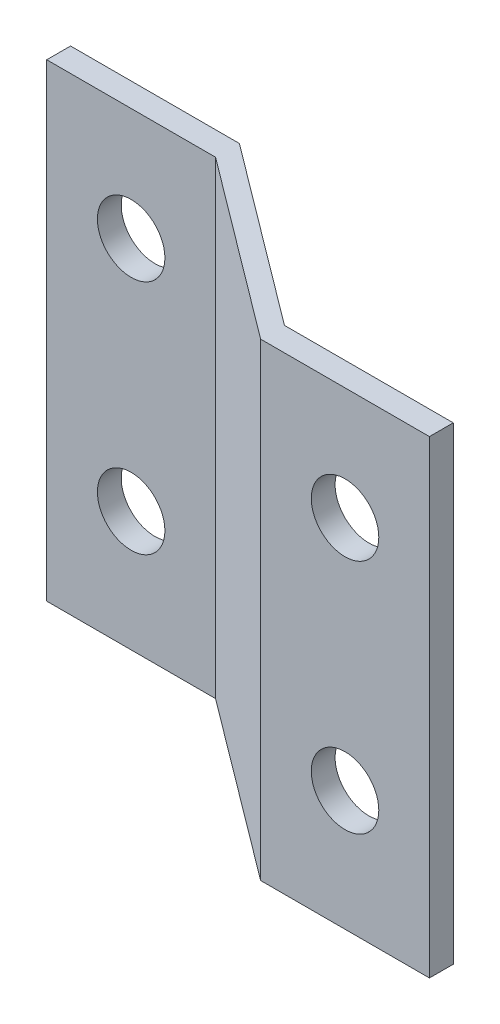
SolidWorks part; units mm, degrees
ref_plane "Front Plane" through (0, 0, 0) normal (0, 0, 1) x (1, 0, 0)
ref_plane "Top Plane" through (0, 0, 0) normal (0, 1, 0) x (1, 0, 0)
ref_plane "Right Plane" through (0, 0, 0) normal (1, 0, 0) x (0, 0, -1)
sketch "Sketch1" plane through (0, 0, 0) normal (0, 1, 0) x (1, 0, 0)
  line L0 (0, 0) -> (36273.1444, 0) construction
  line L1 (-78.2847, 35.988) -> (-78.2847, 29.638)
  line L2 (-78.2847, 29.638) -> (-33.2847, 29.638)
  line L3 (-33.2847, 29.638) -> (14.7243, -6.35)
  line L4 (14.7243, -6.35) -> (59.7243, -6.35)
  line L5 (59.7243, -6.35) -> (59.7243, 0)
  line L6 (59.7243, 0) -> (14.7243, 0)
  line L7 (14.7243, 0) -> (-33.2847, 35.988)
  line L8 (-33.2847, 35.988) -> (-78.2847, 35.988)
  dimension "D1" = 45
  dimension "D2" = 45
  dimension "D3" = 45
  dimension "D4" = 45
  dimension "D5" = 6.35
  dimension "D6" = 6.35
  dimension "D7" = 60
extrude "Boss-Extrude1" add sketch "Sketch1" along normal blind 125
sketch "Sketch4" plane through (0, 0, -29.638) normal (0, 0, 1) x (1, 0, 0)
  line L0 (-78.2847, 125) -> (-33.2847, 125) construction
  line L1 (-78.2847, 125) -> (-78.2847, 0) construction
  circle A0 centre (-55.7847, 95) radius 9
  circle A1 centre (-55.7847, 32) radius 9
  point P18 (0, 0)
  dimension "D1" = 18
  dimension "D3" = 22.5
  dimension "D6" = 22.5
  dimension "D2" = 30
  dimension "D4" = 63
extrude "Cut-Extrude1" cut sketch "Sketch4" against normal through all
sketch "Sketch5" plane through (0, 0, 6.35) normal (0, 0, 1) x (1, 0, 0)
  line L0 (14.7243, 125) -> (59.7243, 125) construction
  line L2 (59.7243, 125) -> (59.7243, 0) construction
  circle A0 centre (37.2243, 95) radius 9
  circle A1 centre (37.2243, 32) radius 9
  dimension "D2" = 18
  dimension "D3" = 30
  dimension "D4" = 22.5
  dimension "D1" = 22.5
  dimension "D5" = 63
extrude "Cut-Extrude2" cut sketch "Sketch5" against normal through all
